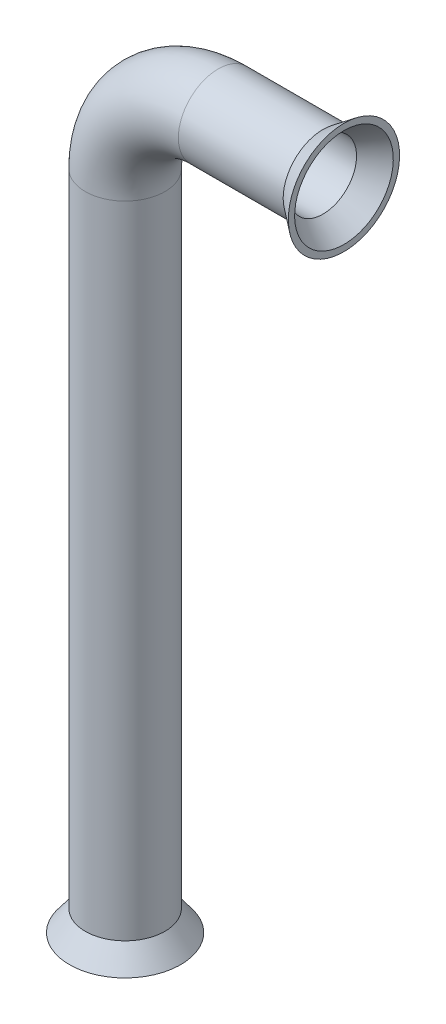
SolidWorks part; units mm, degrees
material "6061-T6 (SS)"
ref_plane "Front Plane" through (0, 0, 0) normal (0, 0, 1) x (1, 0, 0)
ref_plane "Top Plane" through (0, 0, 0) normal (0, 1, 0) x (1, 0, 0)
ref_plane "Right Plane" through (0, 0, 0) normal (1, 0, 0) x (0, 0, -1)
sketch "Sketch1" plane through (0, 0, 0) normal (0, 1, 0) x (1, 0, 0)
  circle A0 centre (0, 0) radius 4.826
  circle A1 centre (0, 0) radius 4.064
  dimension "D1" = 9.652
  dimension "D2" = 8.128
sketch "Sketch2" plane through (0, 0, 0) normal (0, 0, 1) x (1, 0, 0)
  line L0 (0, 0) -> (0, 77.6224)
  line L1 (11.2776, 88.9) -> (23.9776, 88.9)
  arc A0 (0, 77.6224) -> (11.2776, 88.9) centre (11.2776, 77.6224) cw
  dimension "D1" = 88.9
  dimension "D2" = 12.7
  dimension "D3" = 23.9776
sweep "Sweep1" add profiles "Sketch1" path "Sketch2"
sketch "Sketch3" plane through (0, 0, 0) normal (0, -1, 0) x (1, 0, 0)
  circle A0 centre (0, 0) radius 4.826
  circle A1 centre (0, 0) radius 4.826 construction
extrude "Boss-Extrude1" add sketch "Sketch3" along normal blind 2.54 draft 37 draft outward yes
sketch "Sketch4" plane through (0, -2.54, 0) normal (0, -1, 0) x (1, 0, 0)
  line L0 (-4.826, 0) -> (-4.064, 0) construction
  line L1 (-5.978, 0) -> (-6.74, 0) construction
  circle A0 centre (0, 0) radius 5.978
  circle A1 centre (0, 0) radius 4.826 construction
  circle A2 centre (0, 0) radius 4.064 construction
  circle A3 centre (0, 0) radius 6.74 construction
extrude "Cut-Extrude1" cut sketch "Sketch4" against normal through all draft 37
sketch "Sketch5" plane through (23.9776, 0, 0) normal (1, 0, 0) x (0, 0, -1)
  circle A1 centre (0, 88.9) radius 4.826
  circle A2 centre (0, 88.9) radius 4.826 construction
  circle A3 centre (0, 88.9) radius 4.826 construction
extrude "Boss-Extrude2" add sketch "Sketch5" along normal blind 2.54 draft 37 draft outward yes
sketch "Sketch6" plane through (26.5176, 0, 0) normal (1, 0, 0) x (0, 0, -1)
  line L0 (-5.978, 88.9) -> (-6.74, 88.9) construction
  circle A0 centre (0, 88.9) radius 5.978
  circle A1 centre (0, 88.9) radius 6.74 construction
  dimension "D1" = 0.762
extrude "Cut-Extrude2" cut sketch "Sketch6" against normal through all draft 37
